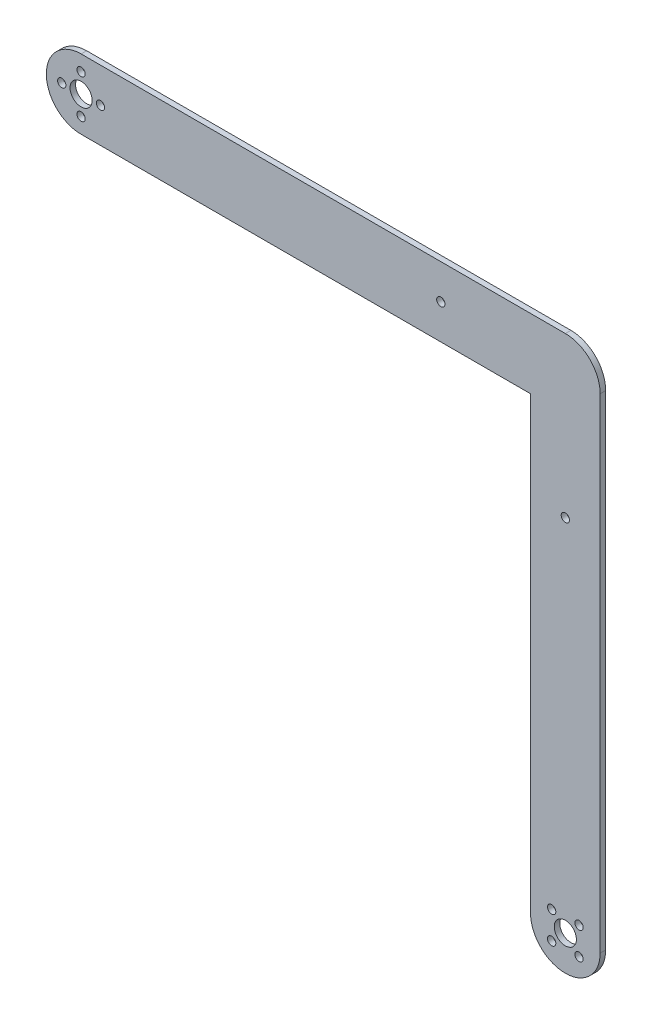
SolidWorks part; units mm, degrees
ref_plane "Front" through (0, 0, 0) normal (0, 0, 1) x (1, 0, 0)
ref_plane "Top" through (0, 0, 0) normal (0, 1, 0) x (1, 0, 0)
ref_plane "Right" through (0, 0, 0) normal (1, 0, 0) x (0, 0, -1)
sketch "草图1" plane through (0, 0, 0) normal (0, 0, 1) x (1, 0, 0)
  line L0 (-12.5857, 0) -> (-12.5857, 162.5)
  line L2 (12.5857, 175.074) -> (12.5857, 0)
  line L3 (-175, 162.5) -> (-12.5857, 162.5)
  line L4 (-175, 187.6479) -> (0.0117, 187.6479)
  arc A0 (-12.5857, 0) -> (12.5857, 0) centre (0, 0) ccw
  circle A2 centre (0, 0) radius 4
  arc A14 (12.5857, 175.074) -> (0.0117, 187.6479) centre (0.0117, 175.074) ccw
  arc A15 (-175, 187.6479) -> (-175, 162.5) centre (-175, 175.074) ccw
  circle A16 centre (-175, 175.074) radius 4
  circle A18 centre (-175, 182.074) radius 1.5
  circle A19 centre (-168, 175.074) radius 1.5
  circle A20 centre (-175, 168.074) radius 1.5
  circle A21 centre (-182, 175.074) radius 1.5
  circle A22 centre (0, 130) radius 1.5
  circle A23 centre (-45, 175.074) radius 1.5
  circle A26 centre (4.9497, 4.9497) radius 1.5
  circle A27 centre (4.9497, -4.9497) radius 1.5
  circle A28 centre (-4.9497, -4.9497) radius 1.5
  circle A29 centre (-4.9497, 4.9497) radius 1.5
  point P16 (0, 0)
  point P35 (-175, 175.074)
  point P40 (0, 0)
extrude "凸台-拉伸2" add sketch "草图1" along normal blind 2
